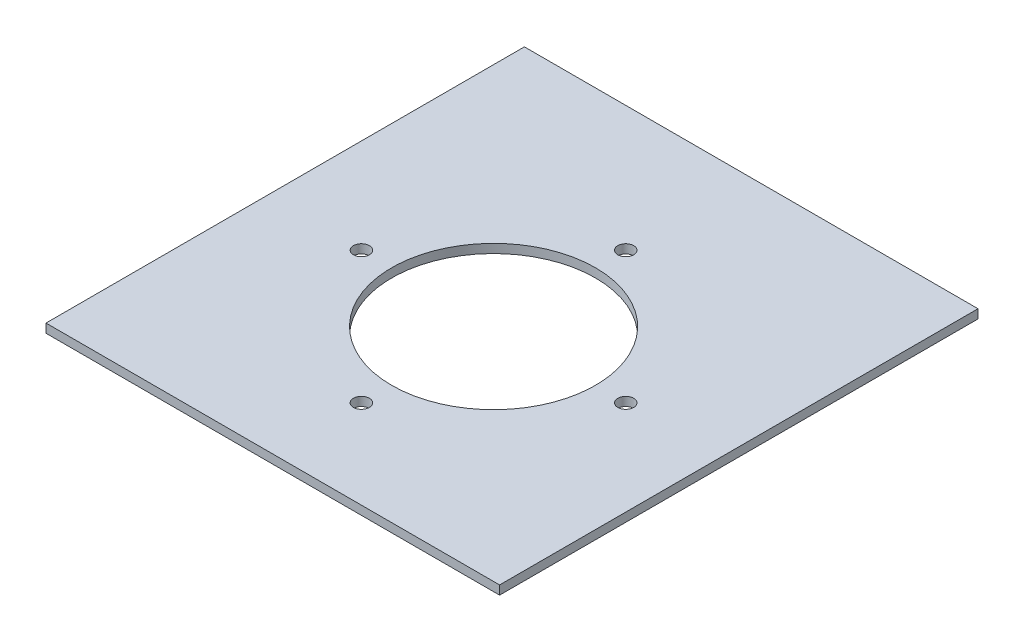
SolidWorks part; units mm, degrees
ref_plane "Płaszczyzna przednia" through (0, 0, 0) normal (0, 0, 1) x (1, 0, 0)
ref_plane "Płaszczyzna górna" through (0, 0, 0) normal (0, 1, 0) x (1, 0, 0)
ref_plane "Płaszczyzna prawa" through (0, 0, 0) normal (1, 0, 0) x (0, 0, -1)
sketch "Szkic1" plane through (0, 0, 0) normal (0, 1, 0) x (1, 0, 0)
  line L1 (0, 0) -> (256, 0)
  line L2 (0, 0) -> (0, 270)
  line L3 (0, 270) -> (256, 270)
  line L4 (256, 0) -> (256, 270)
  dimension "D1" = 270
  dimension "D2" = 256
extrude "Dodanie-wyciągnięcie1" add sketch "Szkic1" along normal blind 5
sketch "Szkic2" plane through (0, 5, 0) normal (0, 1, 0) x (1, 0, 0)
  line L0 (128, 0) -> (128, 270) construction
  line L1 (0, 0) -> (256, 0) construction
  line L2 (256, 270) -> (0, 270) construction
  line L3 (128, 199.2) -> (128, 50) construction
  circle A5 centre (128, 124.6) radius 57.5
  circle A6 centre (128, 124.6) radius 74.6 construction
  circle A7 centre (128, 199.2) radius 4.5
  circle A8 centre (202.6, 124.6) radius 4.5
  circle A9 centre (128, 50) radius 4.5
  circle A10 centre (53.4, 124.6) radius 4.5
  point P10 (66.568, 120.3836)
  point P11 (0, 0)
  point P21 (128, 124.6)
  dimension "D1" = 149.2
  dimension "D5" = 115
  dimension "D3" = 9
  dimension "D2" = 124.6
  dimension "D4" = 4
extrude "Wytnij-wyciągnięcie1" cut sketch "Szkic2" against normal blind 5
